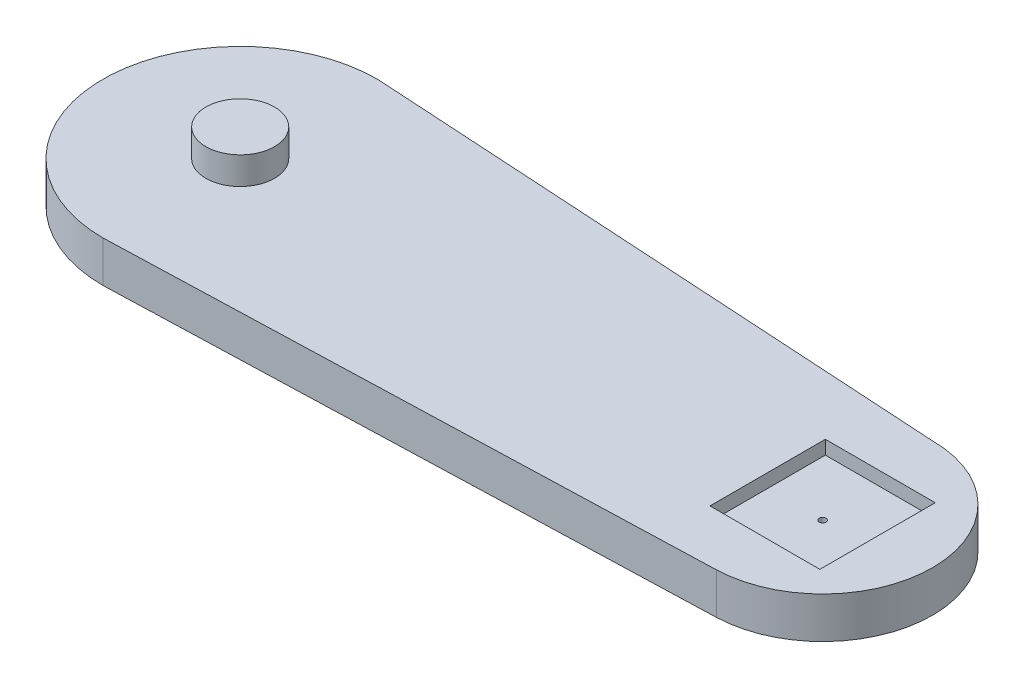
SolidWorks part; units mm, degrees
ref_plane "Alzado" through (0, 0, 0) normal (0, 0, 1) x (1, 0, 0)
ref_plane "Planta" through (0, 0, 0) normal (0, 1, 0) x (1, 0, 0)
ref_plane "Vista lateral" through (0, 0, 0) normal (1, 0, 0) x (0, 0, -1)
sketch "Croquis1" plane through (0, 0, 0) normal (0, 1, 0) x (1, 0, 0)
  line L0 (0, 0) -> (215, -2.9978) construction
  line L1 (0, 50) -> (215, 37.0022)
  line L2 (0, -50) -> (216.2981, -42.9767)
  arc A0 (0, 50) -> (0, -50) centre (0, 0) ccw
  arc A1 (216.2981, -42.9767) -> (215, 37.0022) centre (215, -2.9978) ccw
  circle A2 centre (0, 0) radius 1.25
  circle A3 centre (215, -2.9978) radius 1.25
  dimension "D1" = 100
  dimension "D3" = 80
  dimension "D4" = 2.5
  dimension "D5" = 2.5
  dimension "D2" = 215
extrude "Saliente-Extruir1" add sketch "Croquis1" along normal blind 15
sketch "Croquis2" plane through (0, 15, 0) normal (0, 1, 0) x (1, 0, 0)
  circle A0 centre (0, 0) radius 12.5
  dimension "D1" = 25
extrude "Saliente-Extruir2" add sketch "Croquis2" along normal blind 10
sketch "Croquis3" plane through (0, 0, 0) normal (0, -1, 0) x (-1, 0, 0)
  circle A0 centre (0, 0) radius 11
  dimension "D1" = 22
extrude "Cortar-Extruir1" cut sketch "Croquis3" against normal blind 5
sketch "Croquis4" plane through (0, 15, 0) normal (0, 1, 0) x (1, 0, 0)
  line L1 (195, -23.9978) -> (235, -23.9978)
  line L2 (195, -23.9978) -> (195, 18.0022)
  line L3 (195, 18.0022) -> (235, 18.0022)
  line L4 (235, -23.9978) -> (235, 18.0022)
  line L5 (195, -23.9978) -> (235, 18.0022) construction
  line L6 (195, 18.0022) -> (235, -23.9978) construction
  point P0 (215, -2.9978)
  dimension "D1" = 42
  dimension "D2" = 40
extrude "Cortar-Extruir2" cut sketch "Croquis4" against normal blind 5
